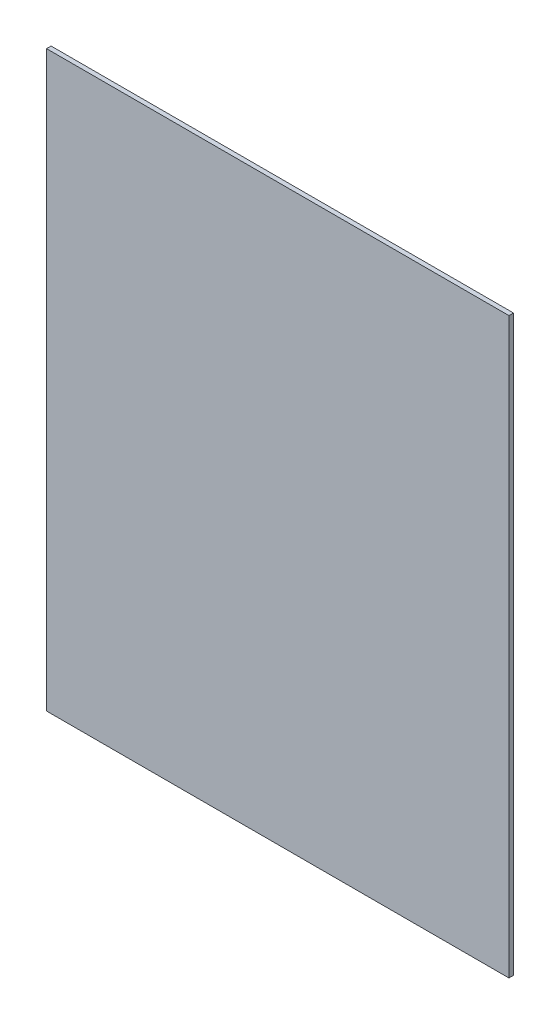
SolidWorks part; units mm, degrees
material "ﾎﾟﾘｴﾁﾚﾝﾃﾚﾌﾀﾗｰﾄ(PET)"
ref_plane "正面" through (0, 0, 0) normal (0, 0, 1) x (1, 0, 0)
ref_plane "平面" through (0, 0, 0) normal (0, 1, 0) x (1, 0, 0)
ref_plane "右側面" through (0, 0, 0) normal (1, 0, 0) x (0, 0, -1)
sketch "ｽｹｯﾁ1" plane through (0, 0, 0) normal (0, 0, 1) x (1, 0, 0)
  line L1 (25.5, -31.635) -> (-25.5, -31.635)
  line L2 (25.5, -31.635) -> (25.5, 31.635)
  line L3 (25.5, 31.635) -> (-25.5, 31.635)
  line L4 (-25.5, -31.635) -> (-25.5, 31.635)
  line L5 (25.5, -31.635) -> (-25.5, 31.635) construction
  line L6 (25.5, 31.635) -> (-25.5, -31.635) construction
  point P0 (0, 0)
  dimension "D1" = 51
  dimension "D2" = 63.27
extrude "ﾎﾞｽ - 押し出し1" add sketch "ｽｹｯﾁ1" along normal blind 0.5
